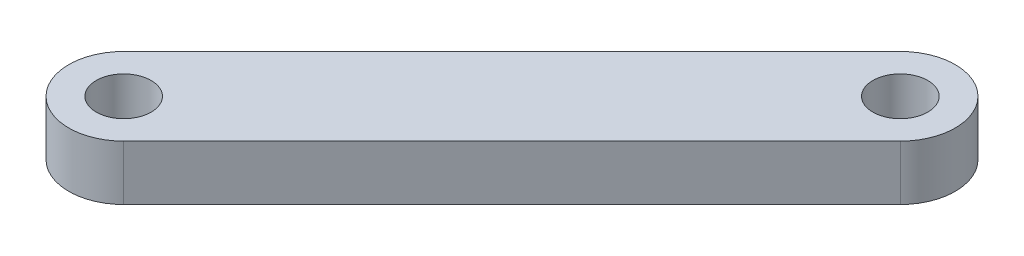
SolidWorks part; units mm, degrees
ref_plane "Ön Düzlem" through (0, 0, 0) normal (0, 0, 1) x (1, 0, 0)
ref_plane "Üst Düzlem" through (0, 0, 0) normal (0, 1, 0) x (1, 0, 0)
ref_plane "Sağ Düzlem" through (0, 0, 0) normal (1, 0, 0) x (0, 0, -1)
sketch "Sketch1" plane through (0, 0, 0) normal (0, 1, 0) x (1, 0, 0)
  line L1 (-7.0711, 7.0711) -> (63.6396, 77.7817)
  line L2 (77.7817, 63.6396) -> (7.0711, -7.0711)
  circle A0 centre (0, 0) radius 5
  arc A1 (-7.0711, 7.0711) -> (7.0711, -7.0711) centre (0, 0) ccw
  circle A2 centre (70.7107, 70.7107) radius 5
  arc A3 (77.7817, 63.6396) -> (63.6396, 77.7817) centre (70.7107, 70.7107) ccw
  dimension "D1" = 10
  dimension "D2" = 10
  dimension "D3" = 10
  dimension "D4" = 10
  dimension "D5" = 100
extrude "Boss-Extrude1" add sketch "Sketch1" along normal blind 10
